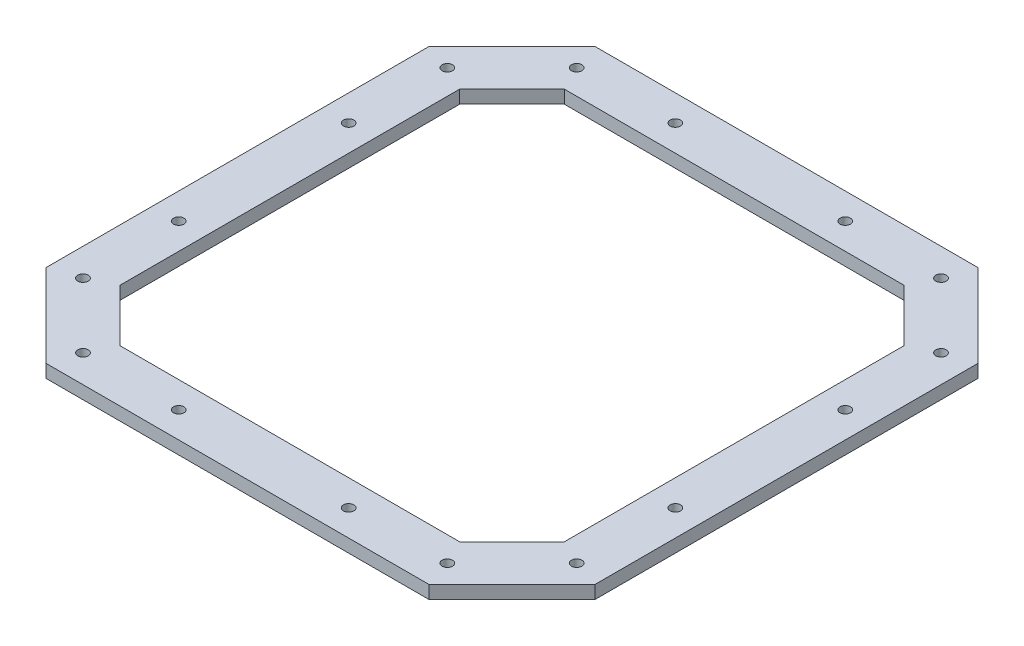
SolidWorks part; units mm, degrees
material "6061-T6 (SS)"
ref_plane "Front Plane" through (0, 0, 0) normal (0, 0, 1) x (1, 0, 0)
ref_plane "Top Plane" through (0, 0, 0) normal (0, 1, 0) x (1, 0, 0)
ref_plane "Right Plane" through (0, 0, 0) normal (1, 0, 0) x (0, 0, -1)
sketch "Sketch1" plane through (0, 0, 0) normal (0, 1, 0) x (1, 0, 0)
  line L0 (65, 85) -> (85, 65)
  line L3 (-65, 85) -> (65, 85)
  line L4 (85, -65) -> (85, 65)
  line L5 (0, 0) -> (85, 85) construction
  line L6 (85, -85) -> (85, -65) construction
  line L7 (65, 85) -> (85, 85) construction
  line L8 (85, 85) -> (85, 65) construction
  line L9 (0, -85) -> (0, 85) construction
  line L10 (-85, 0) -> (85, 0) construction
  line L11 (65, -85) -> (85, -85) construction
  line L12 (0, 0) -> (85, -85) construction
  line L13 (-65, -85) -> (65, -85)
  line L14 (65, -85) -> (85, -65)
  line L15 (0, 0) -> (-85, -85) construction
  line L16 (-65, -85) -> (-85, -85) construction
  line L17 (-85, 85) -> (-85, 65) construction
  line L18 (-65, 85) -> (-85, 85) construction
  line L19 (-85, -85) -> (-85, -65) construction
  line L20 (0, 0) -> (-85, 85) construction
  line L21 (-65, -85) -> (-85, -65)
  line L22 (-85, -65) -> (-85, 65)
  line L23 (-65, 85) -> (-85, 65)
  line L24 (105, -73.2843) -> (105, 73.2843)
  line L25 (73.2843, 105) -> (105, 73.2843)
  line L26 (-73.2843, 105) -> (73.2843, 105)
  line L27 (-73.2843, 105) -> (-105, 73.2843)
  line L28 (-105, -73.2843) -> (-105, 73.2843)
  line L29 (-73.2843, -105) -> (-105, -73.2843)
  line L30 (-73.2843, -105) -> (73.2843, -105)
  line L31 (73.2843, -105) -> (105, -73.2843)
  line L32 (-85, 0) -> (-105, 0) construction
  line L33 (-85, 65) -> (-105, 65) construction
  line L34 (-95, 65) -> (-95, -65) construction
  line L35 (-85, -65) -> (-105, -65) construction
  line L36 (65, 85) -> (65, 105) construction
  line L37 (-65, 95) -> (65, 95) construction
  line L38 (-65, 85) -> (-65, 105) construction
  line L39 (0, 85) -> (0, 105) construction
  line L40 (-65, -85) -> (-65, -105) construction
  line L41 (65, -95) -> (-65, -95) construction
  line L42 (65, -85) -> (65, -105) construction
  line L43 (0, -85) -> (0, -105) construction
  line L44 (85, -65) -> (105, -65) construction
  line L45 (95, 65) -> (95, -65) construction
  line L46 (85, 65) -> (105, 65) construction
  line L47 (85, 0) -> (105, 0) construction
  line L48 (-75, 75) -> (-89.1421, 89.1421) construction
  line L49 (-85, -65) -> (-99.1421, -79.1421) construction
  line L50 (-65, -85) -> (-79.1421, -99.1421) construction
  line L51 (-92.0711, -72.0711) -> (-72.0711, -92.0711) construction
  line L52 (-92.0711, -72.0711) -> (-105, -59.1421) construction
  line L53 (-72.0711, -92.0711) -> (-59.1421, -105) construction
  line L54 (-82.0711, -82.0711) -> (-89.1421, -89.1421) construction
  circle A0 centre (-95, 32.5) radius 2
  circle A1 centre (-95, -32.5) radius 2
  circle A2 centre (32.5, 95) radius 2
  circle A3 centre (-32.5, 95) radius 2
  circle A4 centre (-32.5, -95) radius 2
  circle A5 centre (32.5, -95) radius 2
  circle A6 centre (95, -32.5) radius 2
  circle A7 centre (95, 32.5) radius 2
  circle A12 centre (-94.4454, -69.6967) radius 2
  circle A13 centre (-69.6967, -94.4454) radius 2
  circle A14 centre (69.6967, -94.4454) radius 2
  circle A15 centre (94.4454, -69.6967) radius 2
  circle A16 centre (-94.4454, 69.6967) radius 2
  circle A17 centre (-69.6967, 94.4454) radius 2
  circle A18 centre (69.6967, 94.4454) radius 2
  circle A19 centre (94.4454, 69.6967) radius 2
  point P0 (0, 0)
  point P34 (-95, 0)
  point P46 (0, 95)
  point P56 (0, -95)
  point P66 (95, 0)
  dimension "D4" = 4
  dimension "D5" = 65
  dimension "D6" = 4
  dimension "D7" = 35
  dimension "D1" = 170
  dimension "D2" = 20
  dimension "D3" = 20
extrude "Boss-Extrude1" add sketch "Sketch1" along normal blind 5
